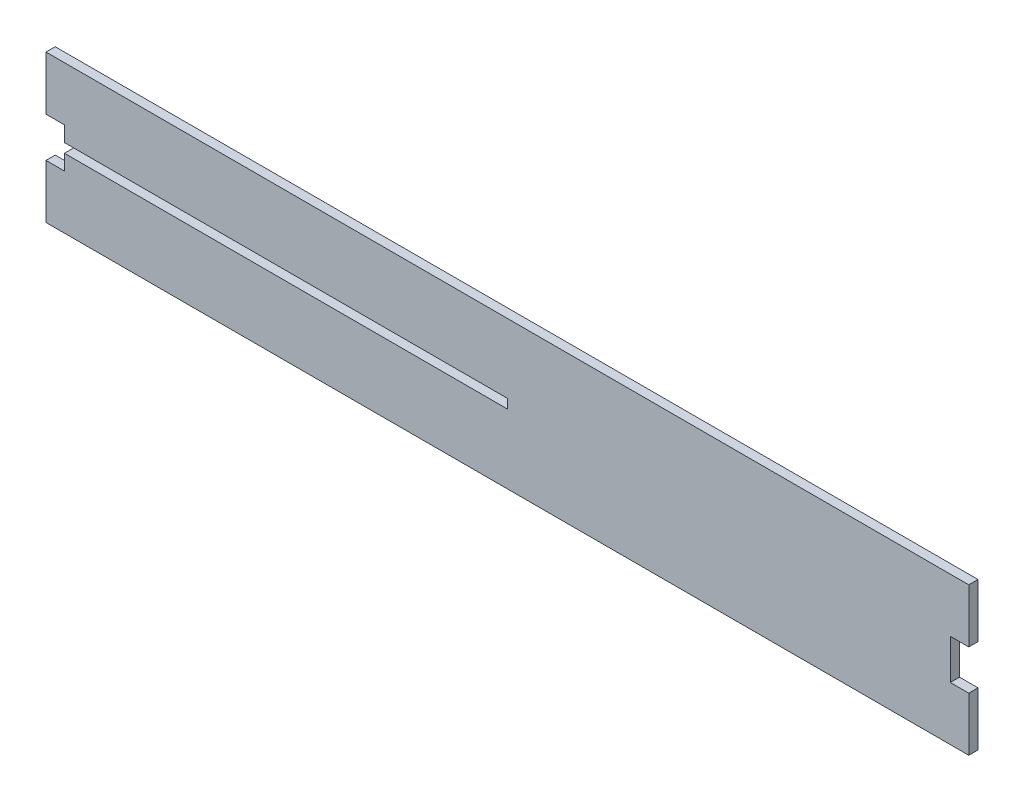
SolidWorks part; units mm, degrees
ref_plane "Alzado" through (0, 0, 0) normal (0, 0, 1) x (1, 0, 0)
ref_plane "Planta" through (0, 0, 0) normal (0, 1, 0) x (1, 0, 0)
ref_plane "Vista lateral" through (0, 0, 0) normal (1, 0, 0) x (0, 0, -1)
sketch "Croquis1" plane through (0, 0, 0) normal (0, 0, 1) x (1, 0, 0)
  line L0 (0, 1.5) -> (0, -1.5)
  line L1 (150, -24) -> (-150, -24)
  line L2 (150, -24) -> (150, -6.5)
  line L3 (150, 24) -> (-150, 24)
  line L4 (-150, -24) -> (-150, -6.5)
  line L5 (150, -24) -> (-150, 24) construction
  line L6 (150, 24) -> (-150, -24) construction
  line L7 (-150, 6.5) -> (-150, 24)
  line L9 (144, -6.5) -> (150, -6.5)
  line L10 (144, -6.5) -> (144, 6.5)
  line L11 (149.9905, -1.4999) -> (-150, 1.5) construction
  line L12 (149.9905, 1.4999) -> (-150, -1.5) construction
  line L13 (0, 1.5) -> (-144, 1.5)
  line L14 (0, -1.5) -> (-144, -1.5)
  line L15 (-144, -6.5) -> (-144, -1.44)
  line L16 (-144, 6.5) -> (-150, 6.5)
  line L17 (-144, -6.5) -> (-150, -6.5)
  line L18 (144, 6.5) -> (150, 6.5)
  line L19 (-144, 1.44) -> (-144, 6.5)
  line L20 (150, 6.5) -> (150, 24)
  point P0 (0, 0)
  point P6 (0, 0)
  dimension "D1" = 48
  dimension "D2" = 3
  dimension "D3" = 300
extrude "Saliente-Extruir1" add sketch "Croquis1" along normal blind 3 contours L0 L14 L4 L1 L2 L3 L7 L13
